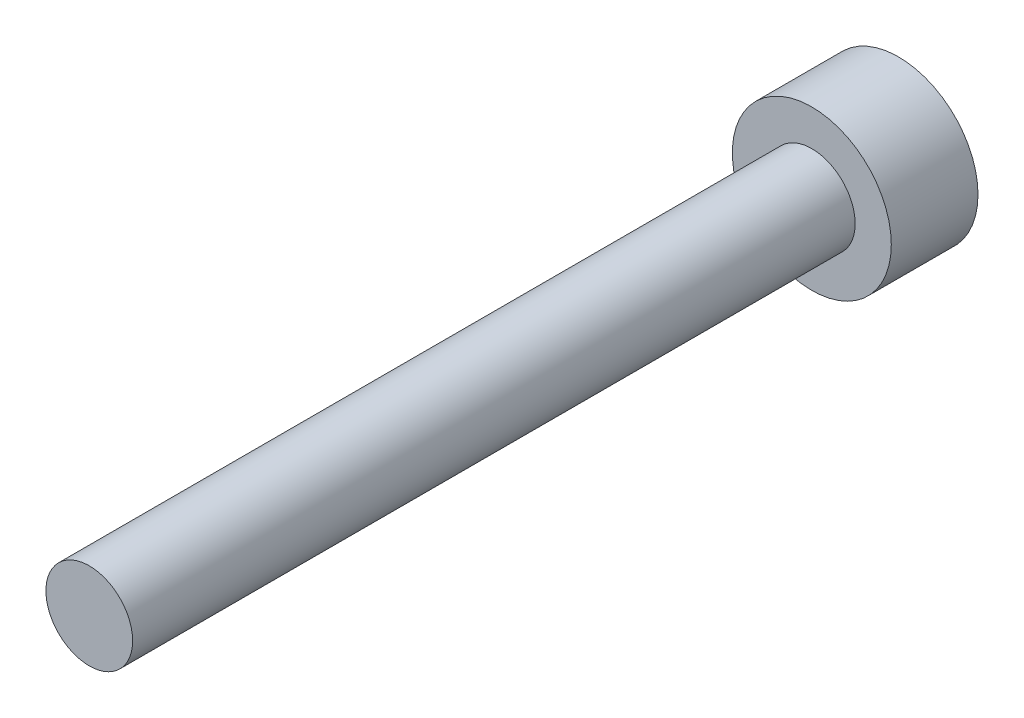
SolidWorks part; units mm, degrees
material "AISI 304"
ref_plane "Alzado" through (0, 0, 0) normal (0, 0, 1) x (1, 0, 0)
ref_plane "Planta" through (0, 0, 0) normal (0, 1, 0) x (1, 0, 0)
ref_plane "Vista lateral" through (0, 0, 0) normal (1, 0, 0) x (0, 0, -1)
sketch "Sk_Cabeza" plane through (0, 0, 0) normal (0, 0, 1) x (1, 0, 0)
  circle A0 centre (0, 0) radius 2.75
  dimension "D1" = 5.5
extrude "Cabeza" add sketch "Sk_Cabeza" along normal blind 3 from offset 3
sketch "Sk_Cuerpo" plane through (0, 0, 0) normal (0, 0, 1) x (1, 0, 0)
  circle A0 centre (0, 0) radius 1.5
  dimension "D1" = 3
extrude "Cuerpo" add sketch "Sk_Cuerpo" along normal blind 25
sketch "Sk_Hexagono_interior" plane through (0, 0, 0) normal (0, 0, 1) x (1, 0, 0)
  line L1 (0, -1.4434) -> (1.25, -0.7217)
  line L2 (1.25, -0.7217) -> (1.25, 0.7217)
  line L3 (1.25, 0.7217) -> (0, 1.4434)
  line L4 (0, 1.4434) -> (-1.25, 0.7217)
  line L5 (-1.25, 0.7217) -> (-1.25, -0.7217)
  line L6 (-1.25, -0.7217) -> (0, -1.4434)
  circle A0 centre (0, 0) radius 1.25 construction
  dimension "D1" = 2.5
extrude "Hexagono_interior" cut sketch "Sk_Hexagono_interior" along normal blind 1.5 from offset 3
